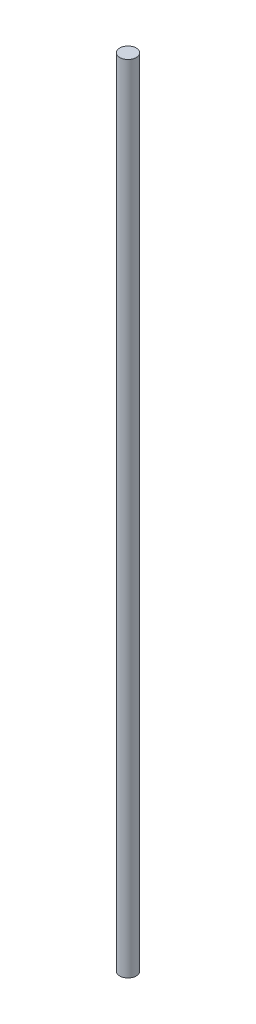
SolidWorks part; units mm, degrees
ref_plane "Front Plane" through (0, 0, 0) normal (0, 0, 1) x (1, 0, 0)
ref_plane "Top Plane" through (0, 0, 0) normal (0, 1, 0) x (1, 0, 0)
ref_plane "Right Plane" through (0, 0, 0) normal (1, 0, 0) x (0, 0, -1)
sketch "Sketch1" plane through (0, 0, 0) normal (0, 1, 0) x (1, 0, 0)
  circle A0 centre (0, 0) radius 3.175
  dimension "D1" = 6.35
extrude "Boss-Extrude1" add sketch "Sketch1" along normal blind 305.562
